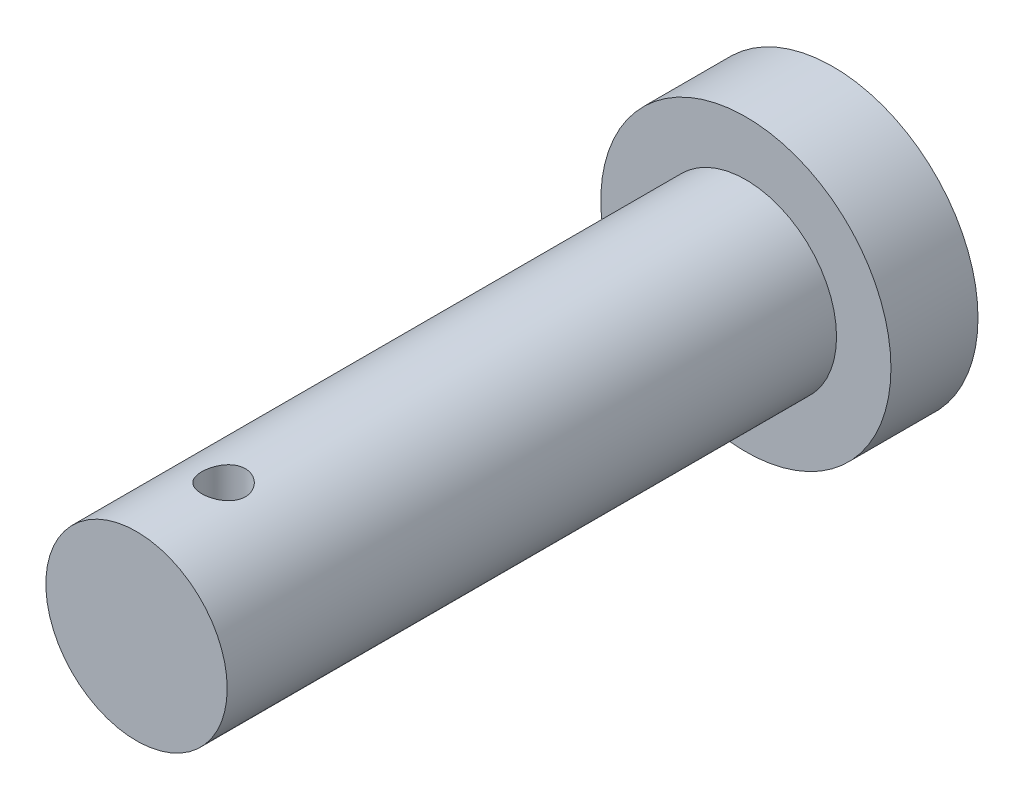
SolidWorks part; units mm, degrees
ref_plane "Front Plane" through (0, 0, 0) normal (0, 0, 1) x (1, 0, 0)
ref_plane "Top Plane" through (0, 0, 0) normal (0, 1, 0) x (1, 0, 0)
ref_plane "Right Plane" through (0, 0, 0) normal (1, 0, 0) x (0, 0, -1)
sketch "Sketch1" plane through (0, 0, 0) normal (0, 0, 1) x (1, 0, 0)
  circle A0 centre (0, 0) radius 20
  dimension "D1" = 40
extrude "Boss-Extrude1" add sketch "Sketch1" along normal blind 12
sketch "Sketch2" plane through (0, 0, 12) normal (0, 0, 1) x (1, 0, 0)
  circle A0 centre (0, 0) radius 12.5
  dimension "D1" = 25
extrude "Boss-Extrude2" add sketch "Sketch2" along normal blind 84
sketch "Sketch3" plane through (0, 0, 0) normal (0, 1, 0) x (1, 0, 0)
  circle A0 centre (0, -84) radius 3
  dimension "D1" = 6
extrude "Cut-Extrude1" cut sketch "Sketch3" against normal mid plane 50 contours A0
